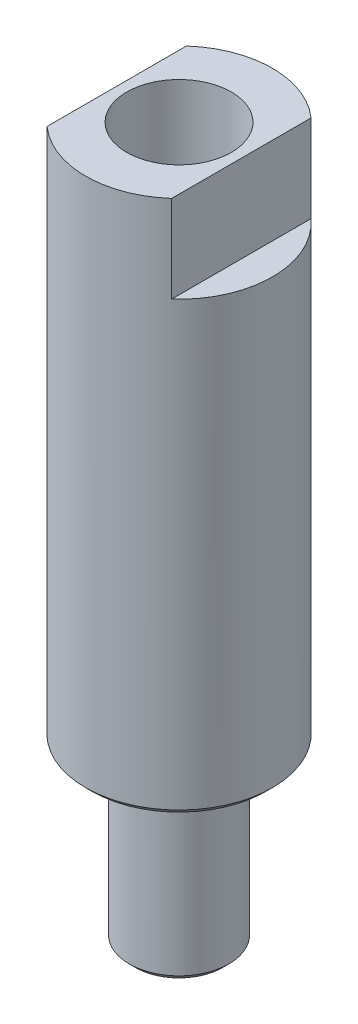
SolidWorks part; units mm, degrees
ref_plane "Front" through (0, 0, 0) normal (0, 0, 1) x (1, 0, 0)
ref_plane "Top" through (0, 0, 0) normal (0, 1, 0) x (1, 0, 0)
ref_plane "Right" through (0, 0, 0) normal (1, 0, 0) x (0, 0, -1)
other "Configuration Table"
sketch "Sketch1" plane through (0, 0, 0) normal (0, 1, 0) x (1, 0, 0)
  circle A0 centre (0, 0) radius 7.5
  dimension "D1" = 15
extrude "Extrude1" add sketch "Sketch1" along normal blind 43
sketch "Sketch2" plane through (0, 0, 0) normal (0, -1, 0) x (1, 0, 0)
  circle A0 centre (0, 0) radius 4
  dimension "D1" = 8
extrude "Extrude2" add sketch "Sketch2" along normal blind 14
sketch "Sketch4" plane through (0, 43, 0) normal (0, 1, 0) x (-1, 0, 0)
  line L0 (5, 5.5902) -> (5, -5.5902)
  line L1 (-5, 5.5902) -> (-5, -5.5902)
  circle A0 centre (0, 0) radius 7.5 construction
  circle A1 centre (0, 0) radius 7.5
  circle M1 centre (0, 0) radius 7.5
  dimension "D1" = 10
extrude "Cut-Extrude1" cut sketch "Sketch4" against normal blind 7 contours L1 M1 | L0 M1
chamfer "Chamfer1" distance 0.5 angle 45 2 edges at (0, -14, -4) (0, 0, 7.5)
sketch "Sketch5" plane through (0, 0, 0) normal (0, 0, 1) x (1, 0, 0)
  line L0 (0, 0) -> (0, 45.4745) construction
  line L1 (0, 43) -> (4.2, 43)
  line L2 (5, 43) -> (-5, 43) construction
  line L3 (4.2, 43) -> (4.2, 25)
  line L4 (4.2, 25) -> (0, 22.4764)
  line L5 (0, 43) -> (0, 22.4764)
  line L6 (0, 43) -> (0, 22.4764)
  dimension "D1" = 4.2
  dimension "D2" = 18
  dimension "D3" = 59
revolve "Cut-Revolve2" cut sketch "Sketch5" angle 360 about L0
